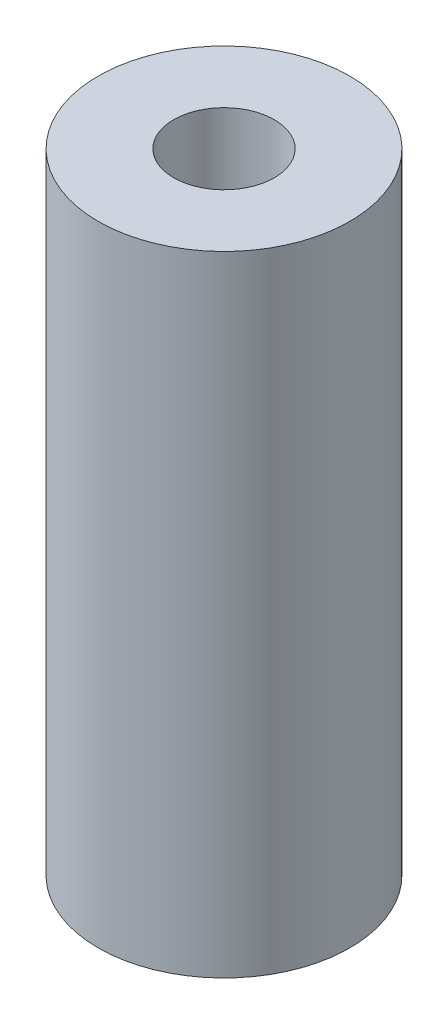
SolidWorks part; units mm, degrees
material "1060 Alloy"
ref_plane "Front" through (0, 0, 0) normal (0, 0, 1) x (1, 0, 0)
ref_plane "Top" through (0, 0, 0) normal (0, 1, 0) x (1, 0, 0)
ref_plane "Right" through (0, 0, 0) normal (1, 0, 0) x (0, 0, -1)
sketch "Sketch1" plane through (0, 0, 0) normal (0, 1, 0) x (1, 0, 0)
  circle A0 centre (0, 0) radius 2.5
  circle A1 centre (0, 0) radius 1
  dimension "D1" = 5
  dimension "D2" = 2
extrude "Boss-Extrude1" add sketch "Sketch1" along normal blind 12.5
